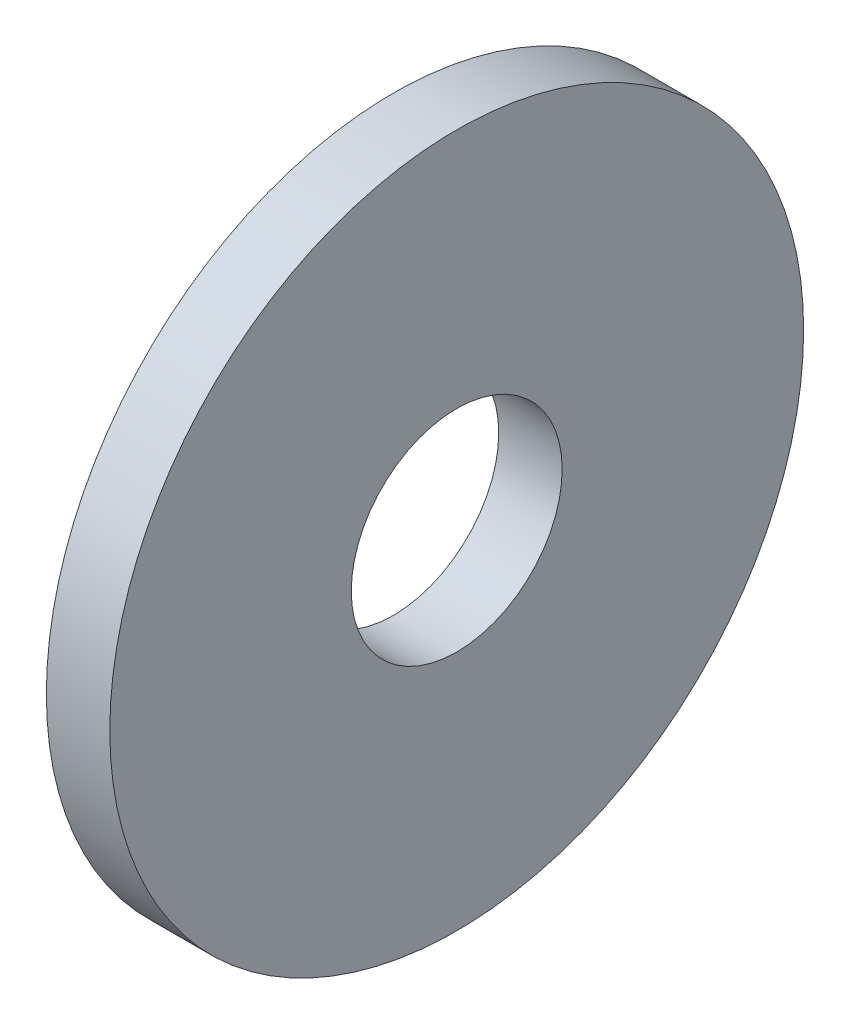
SolidWorks part; units mm, degrees
material "Cast Stainless Steel"
ref_plane "Front Plane" through (0, 0, 0) normal (0, 0, 1) x (1, 0, 0)
ref_plane "Top Plane" through (0, 0, 0) normal (0, 1, 0) x (1, 0, 0)
ref_plane "Right Plane" through (0, 0, 0) normal (1, 0, 0) x (0, 0, -1)
sketch "Sketch1" plane through (0, 0, 0) normal (1, 0, 0) x (0, 0, -1)
  circle A0 centre (0, 0) radius 11.1125
  circle A1 centre (0, 0) radius 3.3782
  dimension "OD" = 22.225
  dimension "ID" = 6.7564
extrude "Boss-Extrude1" add sketch "Sketch1" along normal blind 2.032
